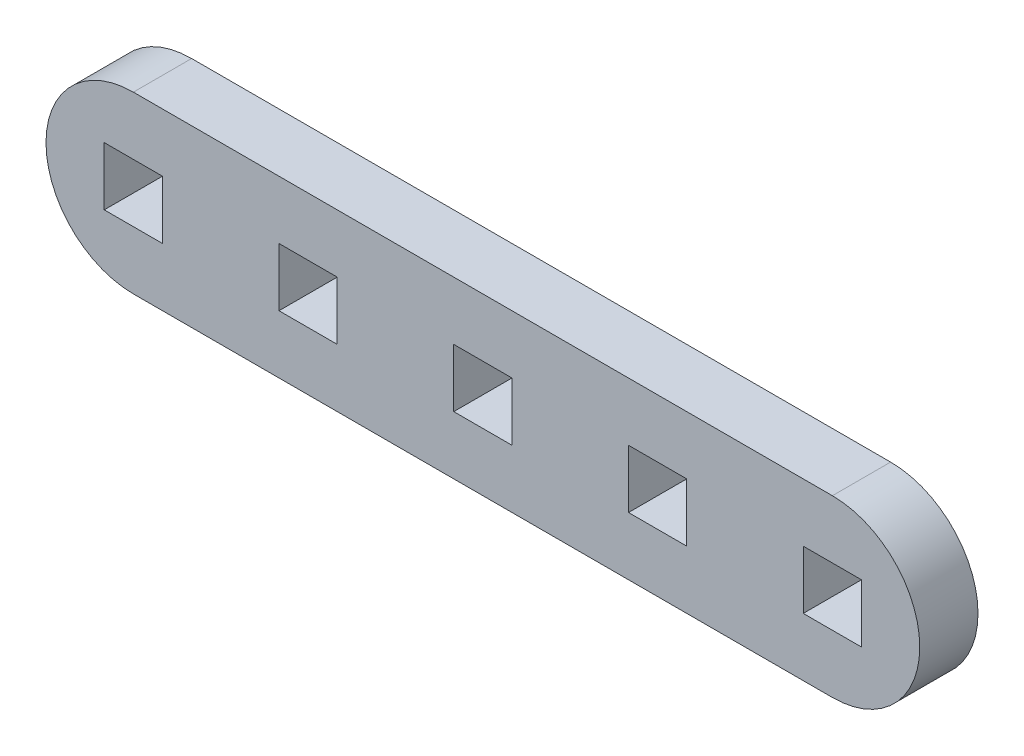
SolidWorks part; units mm, degrees
ref_plane "Alzado" through (0, 0, 0) normal (0, 0, 1) x (1, 0, 0)
ref_plane "Planta" through (0, 0, 0) normal (0, 1, 0) x (1, 0, 0)
ref_plane "Vista lateral" through (0, 0, 0) normal (1, 0, 0) x (0, 0, -1)
sketch "Model" plane through (0, 0, 0) normal (0, 0, 1) x (1, 0, 0)
  line L0 (9.9127, 294.2399) -> (9.9127, 291.2399)
  line L1 (12.9127, 294.2399) -> (9.9127, 294.2399)
  line L2 (12.9127, 291.2399) -> (12.9127, 294.2399)
  line L3 (9.9127, 291.2399) -> (12.9127, 291.2399)
  line L4 (18.9127, 294.2399) -> (18.9127, 291.2399)
  line L5 (21.9127, 294.2399) -> (18.9127, 294.2399)
  line L6 (21.9127, 291.2399) -> (21.9127, 294.2399)
  line L7 (18.9127, 291.2399) -> (21.9127, 291.2399)
  line L8 (27.9127, 294.2399) -> (27.9127, 291.2399)
  line L9 (30.9127, 294.2399) -> (27.9127, 294.2399)
  line L10 (30.9127, 291.2399) -> (30.9127, 294.2399)
  line L11 (27.9127, 291.2399) -> (30.9127, 291.2399)
  line L12 (36.9127, 294.2399) -> (36.9127, 291.2399)
  line L13 (39.9127, 294.2399) -> (36.9127, 294.2399)
  line L14 (39.9127, 291.2399) -> (39.9127, 294.2399)
  line L15 (36.9127, 291.2399) -> (39.9127, 291.2399)
  line L16 (45.9127, 294.2399) -> (45.9127, 291.2399)
  line L17 (48.9127, 294.2399) -> (45.9127, 294.2399)
  line L18 (48.9127, 291.2399) -> (48.9127, 294.2399)
  line L19 (45.9127, 291.2399) -> (48.9127, 291.2399)
  line L20 (11.4127, 297.2399) -> (47.4127, 297.2399)
  line L21 (11.4127, 288.2399) -> (47.4127, 288.2399)
  arc A0 (47.4127, 288.2399) -> (47.4127, 297.2399) centre (47.4127, 292.7399) ccw
  arc A1 (11.4127, 297.2399) -> (11.4127, 288.2399) centre (11.4127, 292.7399) ccw
extrude "Saliente-Extruir1" add sketch "Model" along normal blind 3
